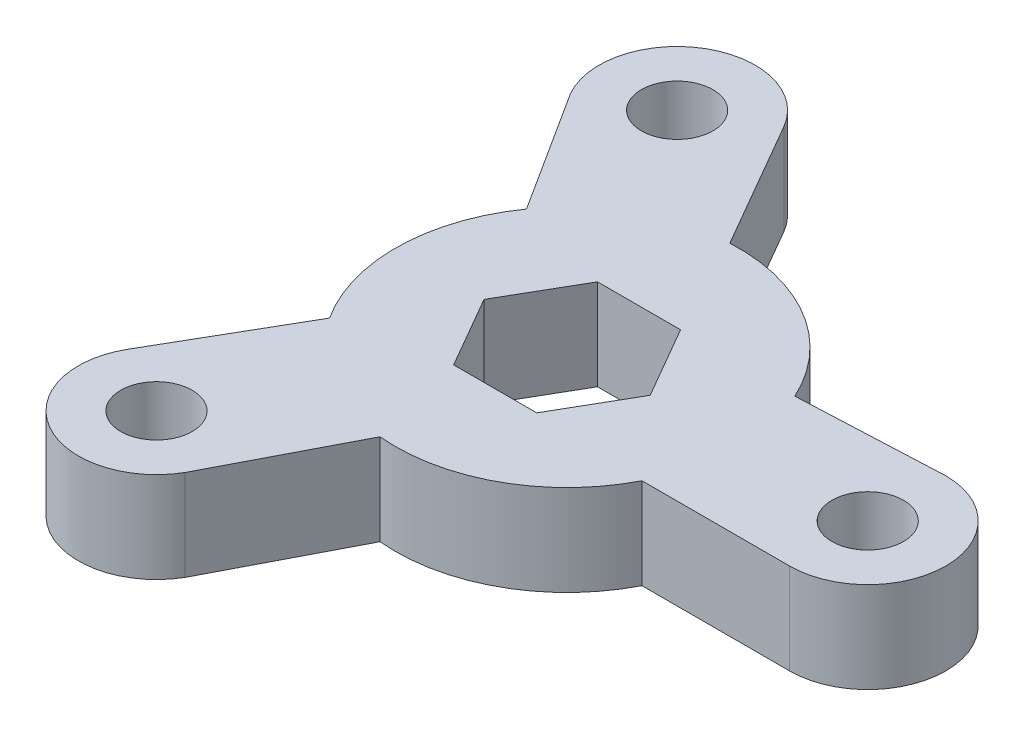
SolidWorks part; units mm, degrees
ref_plane "Front" through (0, 0, 0) normal (0, 0, 1) x (1, 0, 0)
ref_plane "Top" through (0, 0, 0) normal (0, 1, 0) x (1, 0, 0)
ref_plane "Right" through (0, 0, 0) normal (1, 0, 0) x (0, 0, -1)
sketch "Sketch1" plane through (0, 0, 0) normal (0, 1, 0) x (1, 0, 0)
  line L0 (2.5148, 0.2447) -> (13.0148, 0.2447)
  line L1 (2.5148, 0.2447) -> (-2.7352, 9.338)
  line L2 (2.5148, 0.2447) -> (-2.7352, -8.8486)
  line L3 (2.5148, 0.2447) -> (-2.7352, 9.338) construction
  line L10 (2.5148, 0.2447) -> (13.0148, 0.2447) construction
  line L11 (13.0148, -2.4841) -> (7.8583, -2.4841)
  line L12 (13.0148, 2.9736) -> (7.9691, 2.7447)
  line L13 (-5.0985, -7.4841) -> (-2.5203, -3.0185)
  line L14 (-0.372, -10.213) -> (1.9526, -5.7289)
  line L15 (-0.372, 10.7024) -> (2.2062, 6.2368)
  line L16 (-5.0985, 7.9736) -> (-2.3775, 3.7183)
  line L18 (5.4159, 0.2447) -> (3.9654, 2.7572)
  line L19 (3.9654, 2.7572) -> (1.0642, 2.7572)
  line L20 (1.0642, 2.7572) -> (-0.3864, 0.2447)
  line L21 (-0.3864, 0.2447) -> (1.0642, -2.2678)
  line L22 (1.0642, -2.2678) -> (3.9654, -2.2678)
  line L23 (3.9654, -2.2678) -> (5.4159, 0.2447)
  circle A0 centre (-2.7352, 9.338) radius 1.25
  circle A1 centre (13.0148, 0.2447) radius 1.25
  circle A2 centre (-2.7352, -8.8486) radius 1.25
  circle A3 centre (2.5148, 0.2447) radius 2.5125 construction
  arc A4 (-0.372, 10.7024) -> (-5.0985, 7.9736) centre (-2.7352, 9.338) ccw
  circle A5 centre (2.5148, 0.2447) radius 6
  arc A6 (13.0148, -2.4841) -> (13.0148, 2.9736) centre (13.0148, 0.2447) ccw
  arc A7 (-5.0985, -7.4841) -> (-0.372, -10.213) centre (-2.7352, -8.8486) ccw
  point P39 (2.5148, 0.2447)
  dimension "D1" = 3
  dimension "D2" = 120
  dimension "D3" = 3
extrude "Boss-Extrude1" add sketch "Sketch1" along normal blind 3.175
